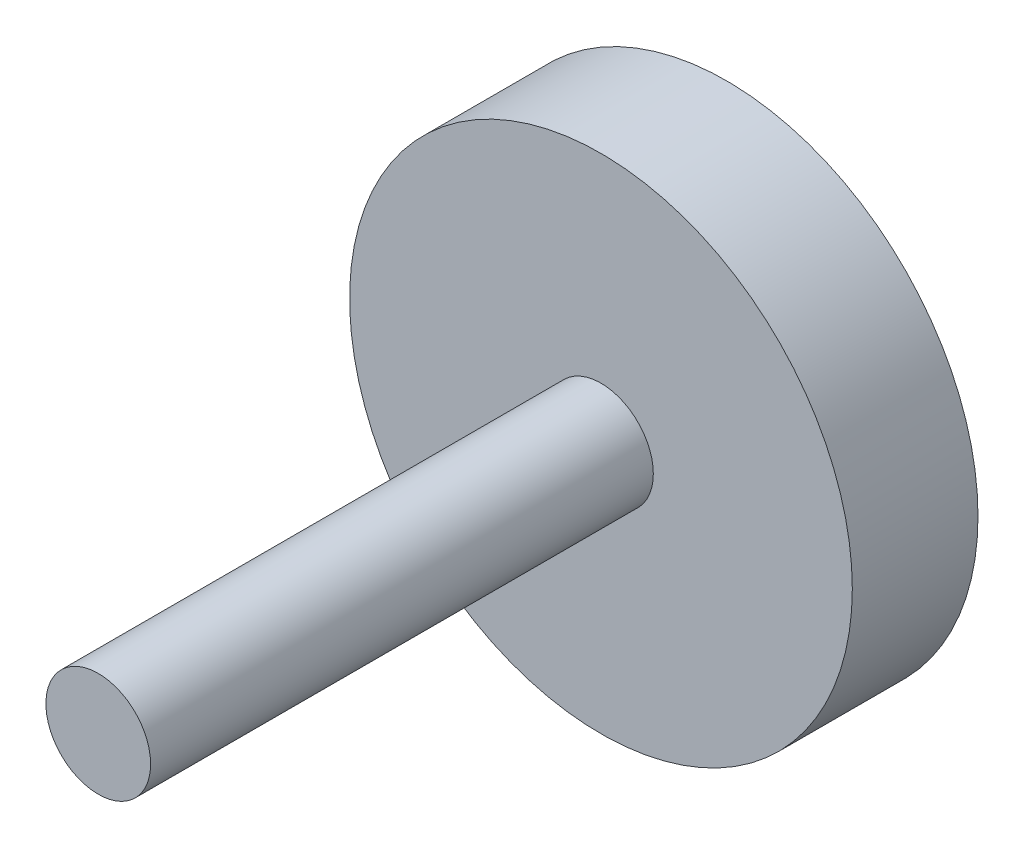
SolidWorks part; units mm, degrees
ref_plane "Front Plane" through (0, 0, 0) normal (1, 0, 0) x (0, 1, 0)
ref_plane "Top Plane" through (0, 0, 0) normal (0, 0, 1) x (0, 1, 0)
ref_plane "Right Plane" through (0, 0, 0) normal (0, 1, 0) x (-1, 0, 0)
sketch "Sketch1" plane through (0, 0, 0) normal (0, 0, 1) x (0, 1, 0)
  circle A0 centre (0, 0) radius 20
  dimension "D1" = 40
extrude "Boss-Extrude1" add sketch "Sketch1" along normal blind 10
sketch "Sketch2" plane through (0, 0, 10) normal (0, 0, 1) x (1, 0, 0)
  circle A0 centre (0, 0) radius 4.1656
  dimension "D1" = 8.3312
extrude "Boss-Extrude2" add sketch "Sketch2" along normal blind 40
